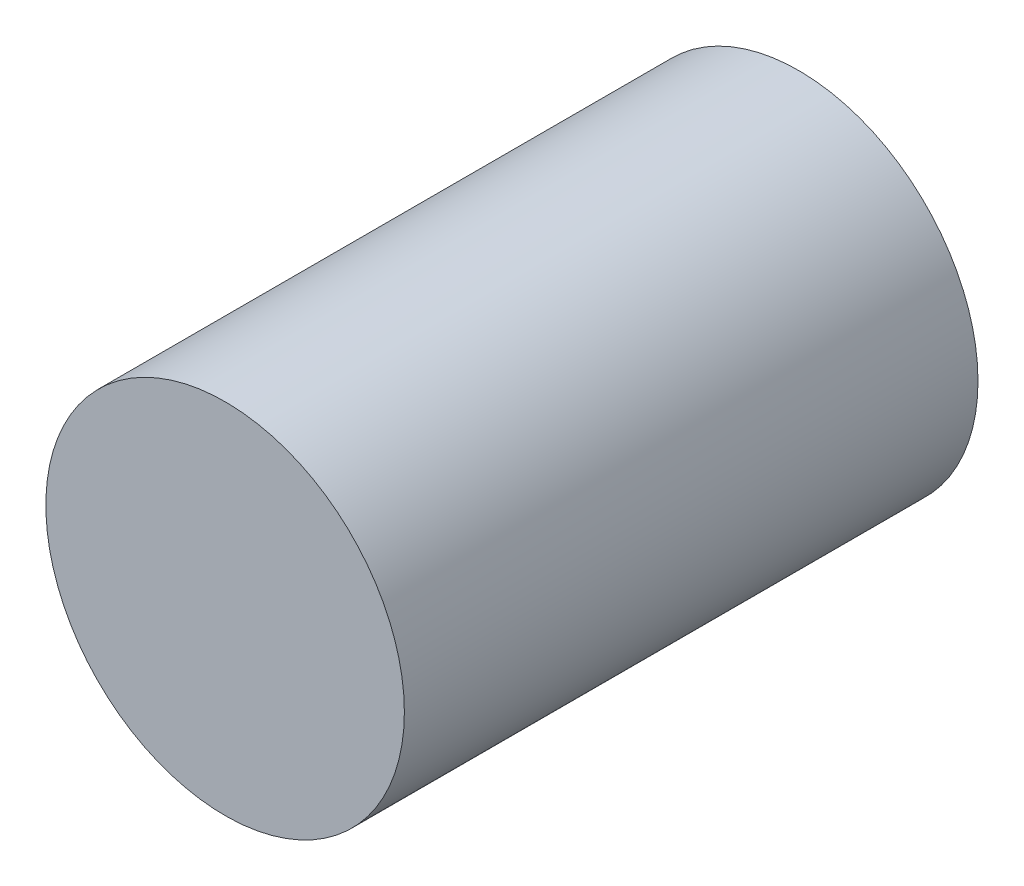
SolidWorks part; units mm, degrees
ref_plane "前视基准面" through (0, 0, 0) normal (0, 0, 1) x (1, 0, 0)
ref_plane "上视基准面" through (0, 0, 0) normal (0, 1, 0) x (1, 0, 0)
ref_plane "右视基准面" through (0, 0, 0) normal (1, 0, 0) x (0, 0, -1)
sketch "草图1" plane through (0, 0, 0) normal (0, 0, 1) x (1, 0, 0)
  circle A0 centre (-5.7977, 10.14) radius 2.5
  dimension "D1" = 5
extrude "凸台-拉伸1" add sketch "草图1" along normal blind 8 contours A0
